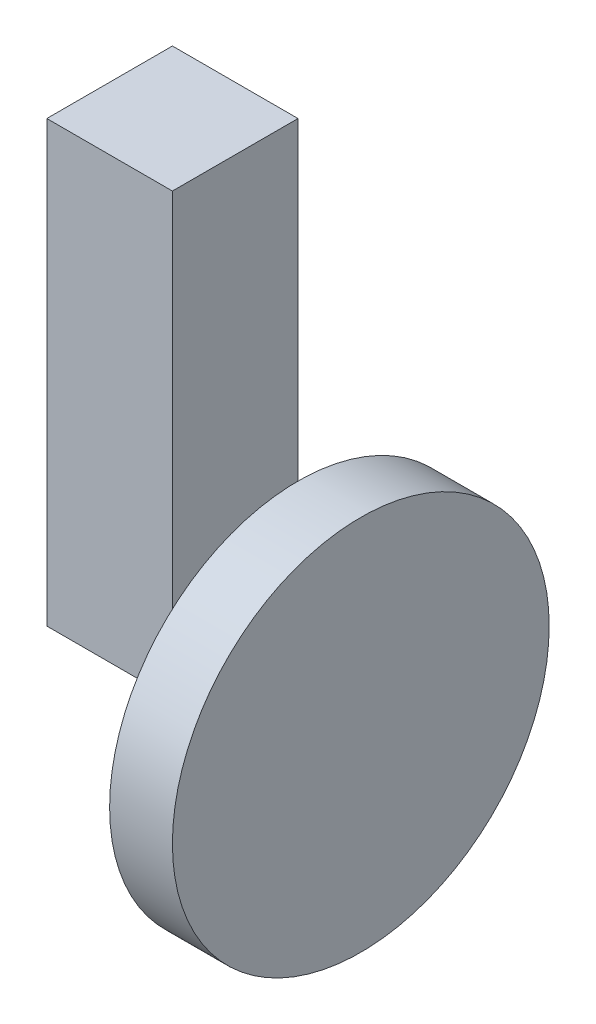
SolidWorks part; units mm, degrees
ref_plane "前视基准面" through (0, 0, 0) normal (0, 0, 1) x (1, 0, 0)
ref_plane "上视基准面" through (0, 0, 0) normal (0, 1, 0) x (1, 0, 0)
ref_plane "右视基准面" through (0, 0, 0) normal (1, 0, 0) x (0, 0, -1)
sketch "草图1" plane through (0, 0, 0) normal (0, 1, 0) x (1, 0, 0)
  line L1 (-10, -10) -> (10, -10)
  line L2 (-10, -10) -> (-10, 10)
  line L3 (-10, 10) -> (10, 10)
  line L4 (10, -10) -> (10, 10)
  line L5 (-10, -10) -> (10, 10) construction
  line L6 (-10, 10) -> (10, -10) construction
  point P0 (0, 0)
extrude "凸台-拉伸1" add sketch "草图1" against normal blind 70
ref_plane "基准面1" through (10, 0, 0) normal (1, 0, 0) x (0, 0, -1)
sketch "草图2" plane through (10, 0, 0) normal (1, 0, 0) x (0, 0, -1)
  line L0 (-10, -70) -> (-10, 0) construction
  line L1 (-10, -60) -> (10, -60)
  line L2 (-10, -60) -> (-10, -80)
  line L3 (-10, -80) -> (10, -80)
  line L4 (10, -60) -> (10, -80)
extrude "凸台-拉伸2" add sketch "草图2" along normal blind 10
ref_plane "基准面3" through (20, 0, 0) normal (1, 0, 0) x (0, 0, -1)
sketch "草图4" plane through (20, 0, 0) normal (1, 0, 0) x (0, 0, -1)
  circle A0 centre (0, -70) radius 30
  circle A1 centre (0, -70) radius 25
extrude "凸台-拉伸5" add sketch "草图4" along normal blind 10 separate body contours A0 | A1
sketch "草图6" plane through (20, 0, 0) normal (1, 0, 0) x (0, 0, -1)
  circle A0 centre (0, -70) radius 25
extrude "凸台-拉伸6" add sketch "草图6" along normal blind 10
